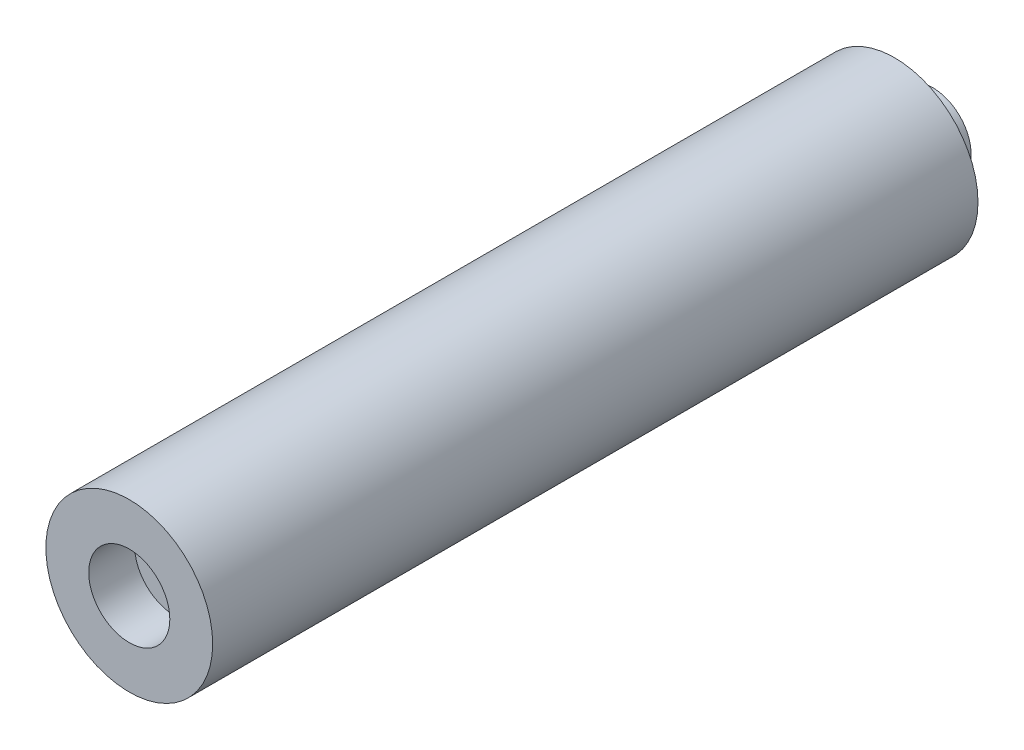
SolidWorks part; units mm, degrees
ref_plane "Front Plane" through (0, 0, 0) normal (0, 0, 1) x (1, 0, 0)
ref_plane "Top Plane" through (0, 0, 0) normal (0, 1, 0) x (1, 0, 0)
ref_plane "Right Plane" through (0, 0, 0) normal (1, 0, 0) x (0, 0, -1)
sketch "Sketch1" plane through (0, 0, 0) normal (0, 0, 1) x (1, 0, 0)
  line L0 (0, -5.45) -> (0, 5.45) construction
  circle A0 centre (0, 0) radius 5.45
  point P6 (0, 0)
  dimension "D1" = 10.9
extrude "Boss-Extrude1" add sketch "Sketch1" along normal blind 50
sketch "Sketch6" plane through (0, 0, 0) normal (0, 0, -1) x (-1, 0, 0)
  circle A0 centre (0, 0) radius 2.5
  dimension "D1" = 5
extrude "Boss-Extrude2" add sketch "Sketch6" along normal blind 2.5
sketch "Sketch7" plane through (0, 0, 50) normal (0, 0, 1) x (1, 0, 0)
  circle A0 centre (0, 0) radius 2.65
  dimension "D1" = 5.3
extrude "Cut-Extrude1" cut sketch "Sketch7" against normal blind 3
